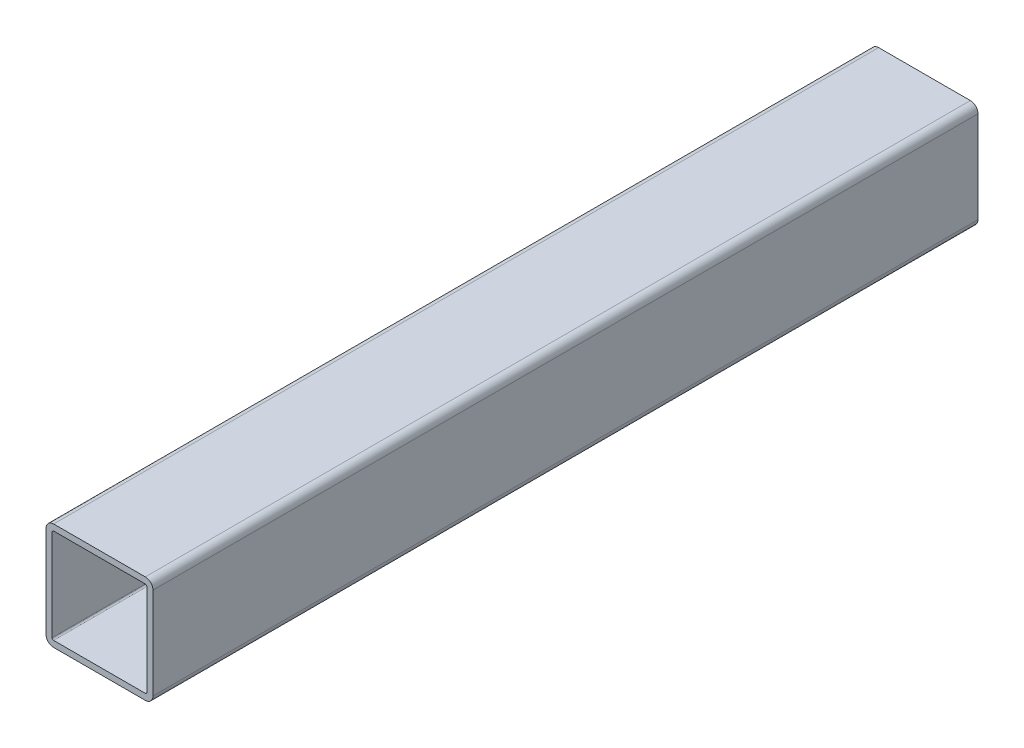
SolidWorks part; units mm, degrees
ref_plane "Front Plane" through (0, 0, 0) normal (0, 0, 1) x (1, 0, 0)
ref_plane "Top Plane" through (0, 0, 0) normal (0, 1, 0) x (1, 0, 0)
ref_plane "Right Plane" through (0, 0, 0) normal (1, 0, 0) x (0, 0, -1)
sketch "Sketch1" plane through (0, 0, 0) normal (0, 0, 1) x (1, 0, 0)
  line L0 (4, 5) -> (4, 65)
  line L1 (5, 0) -> (65, 0)
  line L2 (0, 5) -> (0, 65)
  line L3 (5, 70) -> (65, 70)
  line L4 (70, 5) -> (70, 65)
  line L5 (5, 66) -> (65, 66)
  line L6 (66, 5) -> (66, 65)
  line L7 (5, 4) -> (65, 4)
  arc A0 (5, 0) -> (0, 5) centre (5, 5) cw
  arc A1 (65, 0) -> (70, 5) centre (65, 5) ccw
  arc A2 (65, 70) -> (70, 65) centre (65, 65) cw
  arc A3 (0, 65) -> (5, 70) centre (5, 65) cw
  arc A4 (4, 65) -> (5, 66) centre (5, 65) cw
  arc A5 (65, 66) -> (66, 65) centre (65, 65) cw
  arc A6 (65, 4) -> (66, 5) centre (65, 5) ccw
  arc A7 (5, 4) -> (4, 5) centre (5, 5) cw
  point P7 (0, 0)
  point P12 (70, 70)
  point P15 (0, 70)
  dimension "D3" = 5
  dimension "D1" = 70
  dimension "D2" = 70
  dimension "D4" = 4
extrude "Boss-Extrude1" add sketch "Sketch1" along normal blind 540
